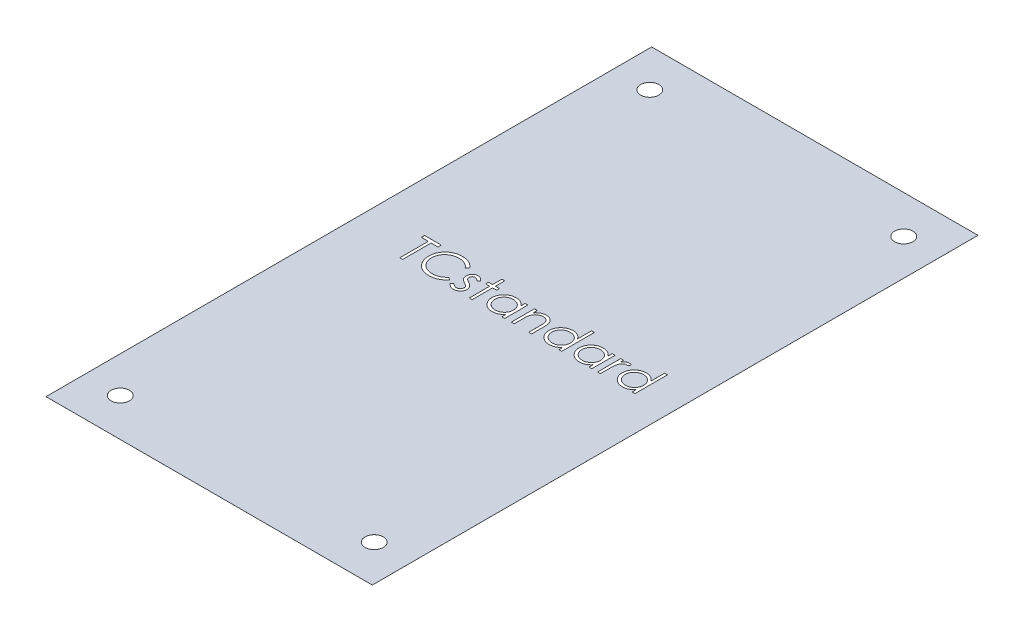
SolidWorks part; units mm, degrees
ref_plane "Front Plane" through (0, 0, 0) normal (0, 0, 1) x (1, 0, 0)
ref_plane "Top Plane" through (0, 0, 0) normal (0, 1, 0) x (1, 0, 0)
ref_plane "Right Plane" through (0, 0, 0) normal (1, 0, 0) x (0, 0, -1)
sketch "Sketch2" plane through (0, 0, 0) normal (0, 1, 0) x (1, 0, 0)
  line L1 (-32.639, -60.579) -> (32.639, -60.579)
  line L2 (-32.639, -60.579) -> (-32.639, 60.579)
  line L3 (-32.639, 60.579) -> (32.639, 60.579)
  line L4 (32.639, -60.579) -> (32.639, 60.579)
  line L5 (-32.639, -60.579) -> (32.639, 60.579) construction
  line L6 (-32.639, 60.579) -> (32.639, -60.579) construction
  point P0 (0, 0)
  dimension "D1" = 121.158
  dimension "D2" = 65.278
extrude "Boss-Extrude1" add sketch "Sketch2" along normal blind 0.0025
sketch "Sketch3" plane through (0, 0.0025, 0) normal (0, 1, 0) x (1, 0, 0)
  line L1 (-25.4, -52.959) -> (25.4, -52.959)
  line L2 (-25.4, -52.959) -> (-25.4, 52.959)
  line L3 (-25.4, 52.959) -> (25.4, 52.959)
  line L4 (25.4, -52.959) -> (25.4, 52.959)
  line L5 (-25.4, -52.959) -> (25.4, 52.959) construction
  line L6 (-25.4, 52.959) -> (25.4, -52.959) construction
  circle A0 centre (-25.4, 52.959) radius 1.8288
  circle A10 centre (25.4, 52.959) radius 1.8288
  circle A11 centre (25.4, -52.959) radius 1.8288
  circle A12 centre (-25.4, -52.959) radius 1.8288
  circle A13 centre (-22.86, 52.959) radius 1.8288
  point P0 (0, 0)
  dimension "D3" = 3.6576
  dimension "D1" = 105.918
  dimension "D2" = 50.8
  dimension "D4" = 2
  dimension "D5" = 2
  dimension "D6" = 2
extrude "Cut-Extrude1" cut sketch "Sketch3" against normal through all contours A12 | A11 | A10 | A0
sketch "Sketch5" plane through (0, 0.0025, 0) normal (0, 1, 0) x (1, 0, 0)
  text T0 "TCstandard\r\n" font "Century Gothic" height 6.35
  point P1 (-15.2212, 0)
extrude "Cut-Extrude2" cut sketch "Sketch5" against normal blind 2.54
